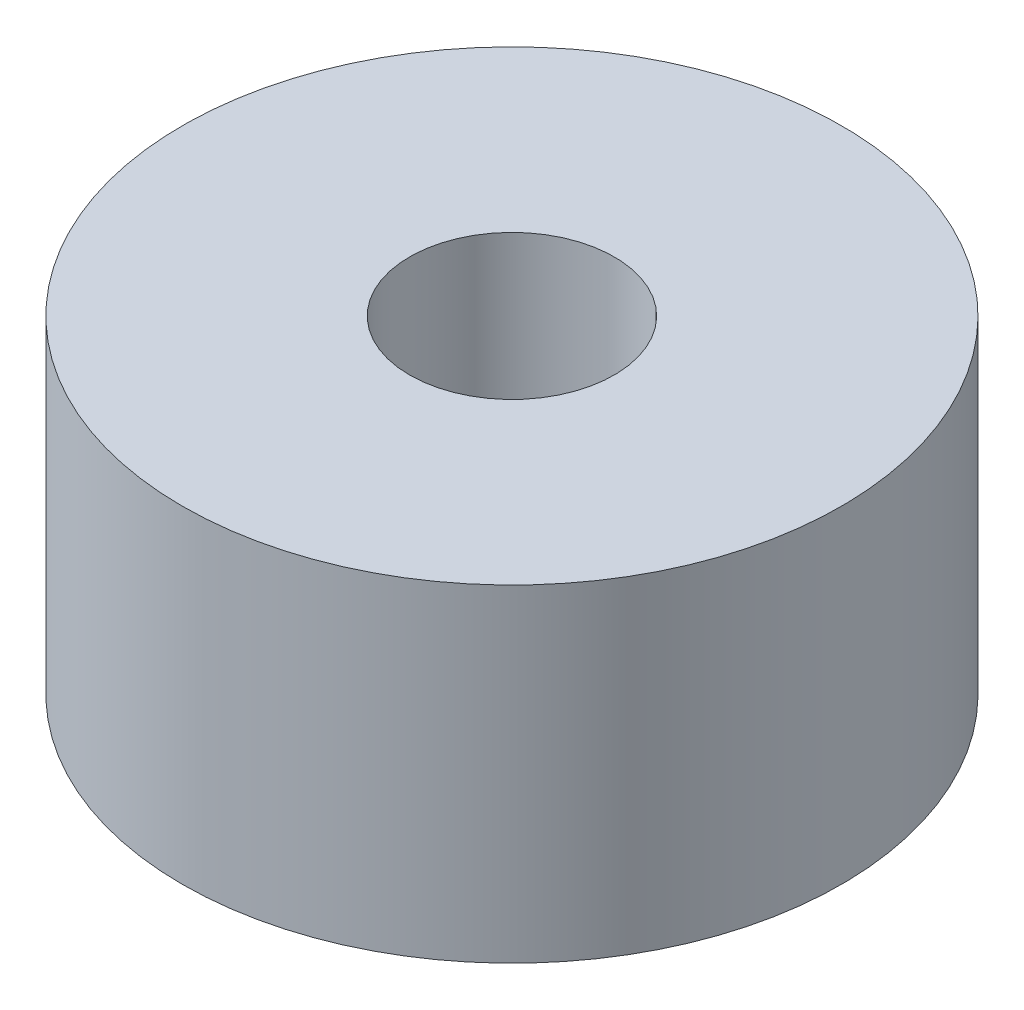
SolidWorks part; units mm, degrees
ref_plane "Front Plane" through (0, 0, 0) normal (0, 0, 1) x (1, 0, 0)
ref_plane "Top Plane" through (0, 0, 0) normal (0, 1, 0) x (1, 0, 0)
ref_plane "Right Plane" through (0, 0, 0) normal (1, 0, 0) x (0, 0, -1)
sketch "Sketch1" plane through (0, 0, 0) normal (0, 1, 0) x (1, 0, 0)
  circle A0 centre (0, 0) radius 16.1
extrude "Boss-Extrude1" add sketch "Sketch1" along normal blind 16
sketch "Sketch2" plane through (0, 16, 0) normal (0, 1, 0) x (1, 0, 0)
  circle A0 centre (0, 0) radius 5
extrude "Cut-Extrude1" cut sketch "Sketch2" against normal through all
